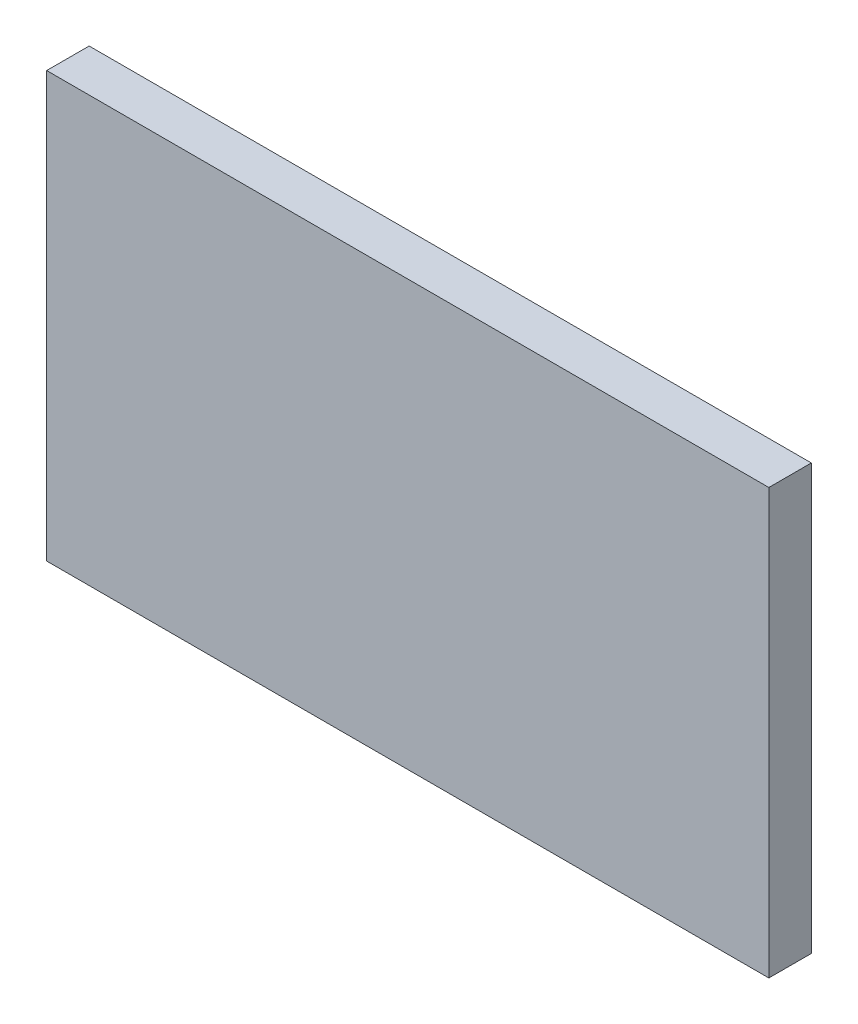
SolidWorks part; units mm, degrees
ref_plane "Plan de face" through (0, 0, 0) normal (0, 0, 1) x (1, 0, 0)
ref_plane "Plan de dessus" through (0, 0, 0) normal (0, 1, 0) x (1, 0, 0)
ref_plane "Plan de droite" through (0, 0, 0) normal (1, 0, 0) x (0, 0, -1)
sketch "Esquisse1" plane through (0, 0, 0) normal (0, 0, 1) x (1, 0, 0)
  line L1 (0, 0) -> (-102, 0)
  line L2 (0, 0) -> (0, 60)
  line L3 (0, 60) -> (-102, 60)
  line L4 (-102, 0) -> (-102, 60)
  dimension "D1" = 60
  dimension "D2" = 102
extrude "Boss.-Extru.1" add sketch "Esquisse1" along normal blind 6
